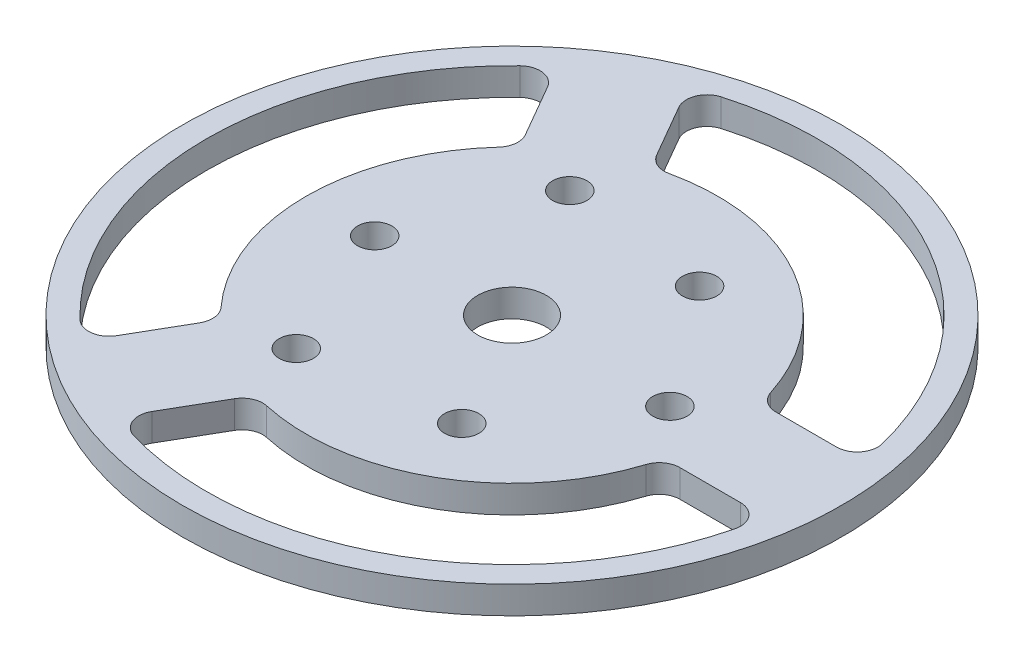
SolidWorks part; units mm, degrees
material "1060 Alloy"
ref_plane "Front Plane" through (0, 0, 0) normal (0, 0, 1) x (1, 0, 0)
ref_plane "Top Plane" through (0, 0, 0) normal (0, 1, 0) x (1, 0, 0)
ref_plane "Right Plane" through (0, 0, 0) normal (1, 0, 0) x (0, 0, -1)
sketch "Sketch1" plane through (0, 0, 0) normal (0, 1, 0) x (1, 0, 0)
  circle A0 centre (0, 0) radius 2
  circle A2 centre (0, 0) radius 24
  circle A3 centre (11.5, 0) radius 1.5
  circle A4 centre (-5.75, -9.9593) radius 1.5
  circle A5 centre (-5.75, 9.9593) radius 1.5
  point P13 (0, 0)
  dimension "D1" = 4
  dimension "D3" = 48
  dimension "D4" = 3
  dimension "D5" = 11.5
  dimension "D6" = 3
extrude "Boss-Extrude1" add sketch "Sketch1" along normal blind 2
sketch "Sketch2" plane through (0, 2, 0) normal (0, 1, 0) x (1, 0, 0)
  line L0 (21.973, 3.5) -> (14.586, 3.5)
  line L1 (21.973, -3.5) -> (14.586, -3.5)
  line L2 (-7.9554, -20.7792) -> (-4.2619, -14.3818)
  line L3 (-14.0176, -17.2792) -> (-10.3241, -10.8818)
  line L4 (-14.0176, 17.2792) -> (-10.3241, 10.8818)
  line L5 (-7.9554, 20.7792) -> (-4.2619, 14.3818)
  arc A0 (-14.0176, 17.2792) -> (-14.0176, -17.2792) centre (0, 0) ccw
  arc A1 (-10.3241, 10.8818) -> (-10.3241, -10.8818) centre (0, 0) ccw
  circle A2 centre (11.5, 0) radius 1.5 construction
  arc A3 (-4.2619, -14.3818) -> (14.586, -3.5) centre (0, 0) ccw
  arc A4 (-7.9554, -20.7792) -> (21.973, -3.5) centre (0, 0) ccw
  arc A5 (14.586, 3.5) -> (-4.2619, 14.3818) centre (0, 0) ccw
  arc A6 (21.973, 3.5) -> (-7.9554, 20.7792) centre (0, 0) ccw
  point P20 (0, 0)
  dimension "D1" = 44.5
  dimension "D2" = 30
  dimension "D3" = 3.5
  dimension "D4" = 3.5
  dimension "D5" = 3
extrude "Cut-Extrude1" cut sketch "Sketch2" against normal blind 2
fillet "Fillet1" radius 1.5 12 edges at (-4.2619, 1, 14.3818) (-7.9554, 1, -20.7792) (14.586, 1, 3.5) (21.973, 1, -3.5) (-14.0176, 1, 17.2792) (-4.2619, 1, -14.3818) (14.586, 1, -3.5) (-7.9554, 1, 20.7792) (21.973, 1, 3.5) (-10.3241, 1, 10.8818) (-10.3241, 1, -10.8818) (-14.0176, 1, -17.2792)
sketch "Sketch3" plane through (0, 2, 0) normal (0, 1, 0) x (1, 0, 0)
  line L0 (0, 0) -> (28.6123, 0) construction
  line L1 (0, 0) -> (7.5, 12.9904) construction
  circle A0 centre (5, 8.6603) radius 1.75
  arc A1 (14.2947, 4.5455) -> (-3.2109, 14.6523) centre (0, 0) ccw construction
  circle A2 centre (0, 0) radius 2 construction
  circle A3 centre (5, -8.6603) radius 1.75
  circle A4 centre (-10, 0) radius 1.75
  point P17 (0, 0)
  dimension "D1" = 3.5
  dimension "D2" = 10
  dimension "D3" = 3
extrude "Cut-Extrude2" cut sketch "Sketch3" against normal blind 10
scale "Scale1" scale about centroid uniform scaling yes scale factor 2
sketch "Sketch4" plane through (0, 3, 0) normal (0, 1, 0) x (1, 0, 0)
  circle A0 centre (0, 0) radius 5
  dimension "D1" = 10
extrude "Cut-Extrude3" cut sketch "Sketch4" against normal blind 10
sketch "Sketch5" plane through (0, 3, 0) normal (0, 1, 0) x (1, 0, 0)
  circle A0 centre (10, 17.3205) radius 2.5
  circle A1 centre (10, 17.3205) radius 6.5472
  circle A2 centre (10, -17.3205) radius 2.5
  circle A3 centre (10, -17.3205) radius 6.5472
  circle A4 centre (-20, 0) radius 2.5
  circle A5 centre (-20, 0) radius 6.5472
  circle A6 centre (-11.5, 19.9186) radius 2.5
  circle A7 centre (-11.5, 19.9186) radius 5.0649
  circle A8 centre (23, 0) radius 2.5
  circle A9 centre (23, 0) radius 5.0649
  circle A10 centre (-11.5, -19.9186) radius 2.5
  circle A11 centre (-11.5, -19.9186) radius 5.0649
  point P12 (0, 0)
  point P23 (0, 0)
  dimension "D1" = 5
  dimension "D2" = 3
  dimension "D3" = 5
  dimension "D4" = 3
extrude "Boss-Extrude2" add sketch "Sketch5" against normal up to surface (4 mm away) up to face at (0, -1, 5)
